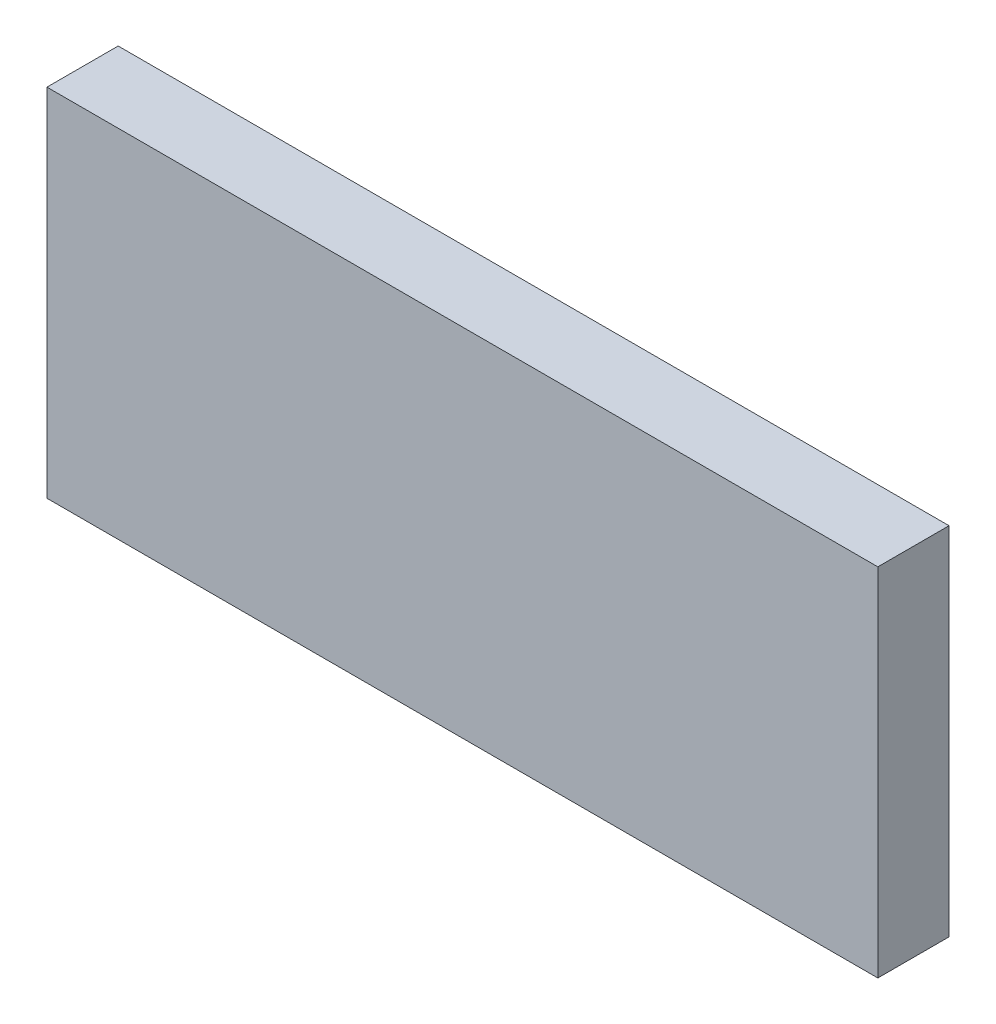
SolidWorks part; units mm, degrees
ref_plane "Front Plane" through (0, 0, 0) normal (0, 0, 1) x (1, 0, 0)
ref_plane "Top Plane" through (0, 0, 0) normal (0, 1, 0) x (1, 0, 0)
ref_plane "Right Plane" through (0, 0, 0) normal (1, 0, 0) x (0, 0, -1)
sketch "Sketch1" plane through (0, 0, 0) normal (0, 0, 1) x (1, 0, 0)
  line L1 (0, 0) -> (70, 0)
  line L2 (0, 0) -> (0, 30)
  line L3 (0, 30) -> (70, 30)
  line L4 (70, 0) -> (70, 30)
  dimension "D1" = 30
  dimension "D2" = 70
extrude "Boss-Extrude1" add sketch "Sketch1" along normal blind 6
